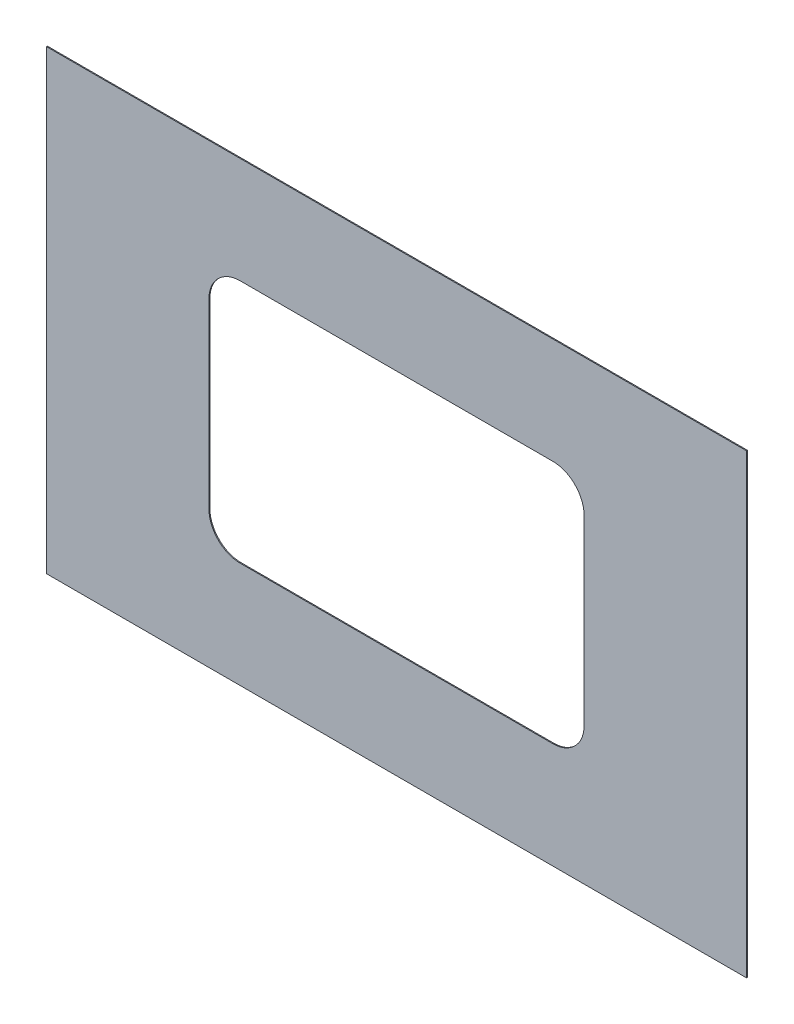
SolidWorks part; units mm, degrees
ref_plane "Front Plane" through (0, 0, 0) normal (0, 0, 1) x (1, 0, 0)
ref_plane "Top Plane" through (0, 0, 0) normal (0, 1, 0) x (1, 0, 0)
ref_plane "Right Plane" through (0, 0, 0) normal (1, 0, 0) x (0, 0, -1)
sketch "Sketch1" plane through (0, 0, 0) normal (0, 0, 1) x (1, 0, 0)
  line L1 (560, 365) -> (-560, 365)
  line L2 (560, 365) -> (560, -365)
  line L3 (560, -365) -> (-560, -365)
  line L4 (-560, 365) -> (-560, -365)
  line L5 (560, 365) -> (-560, -365) construction
  line L6 (560, -365) -> (-560, 365) construction
  line L7 (250, 195.5357) -> (-250, 195.5357)
  line L8 (300, 145.5357) -> (300, -145.5357)
  line L9 (250, -195.5357) -> (-250, -195.5357)
  line L10 (-300, 145.5357) -> (-300, -145.5357)
  line L11 (300, 195.5357) -> (-300, -195.5357) construction
  line L12 (300, -195.5357) -> (-300, 195.5357) construction
  arc A0 (-250, -195.5357) -> (-300, -145.5357) centre (-250, -145.5357) cw
  arc A1 (300, -145.5357) -> (250, -195.5357) centre (250, -145.5357) cw
  arc A2 (300, 145.5357) -> (250, 195.5357) centre (250, 145.5357) ccw
  arc A3 (-250, 195.5357) -> (-300, 145.5357) centre (-250, 145.5357) ccw
  point P0 (0, 0)
  point P6 (0, 0)
  dimension "D3" = 50
  dimension "D1" = 730
  dimension "D2" = 1120
extrude "Boss-Extrude2" add sketch "Sketch1" along normal blind 1.5
